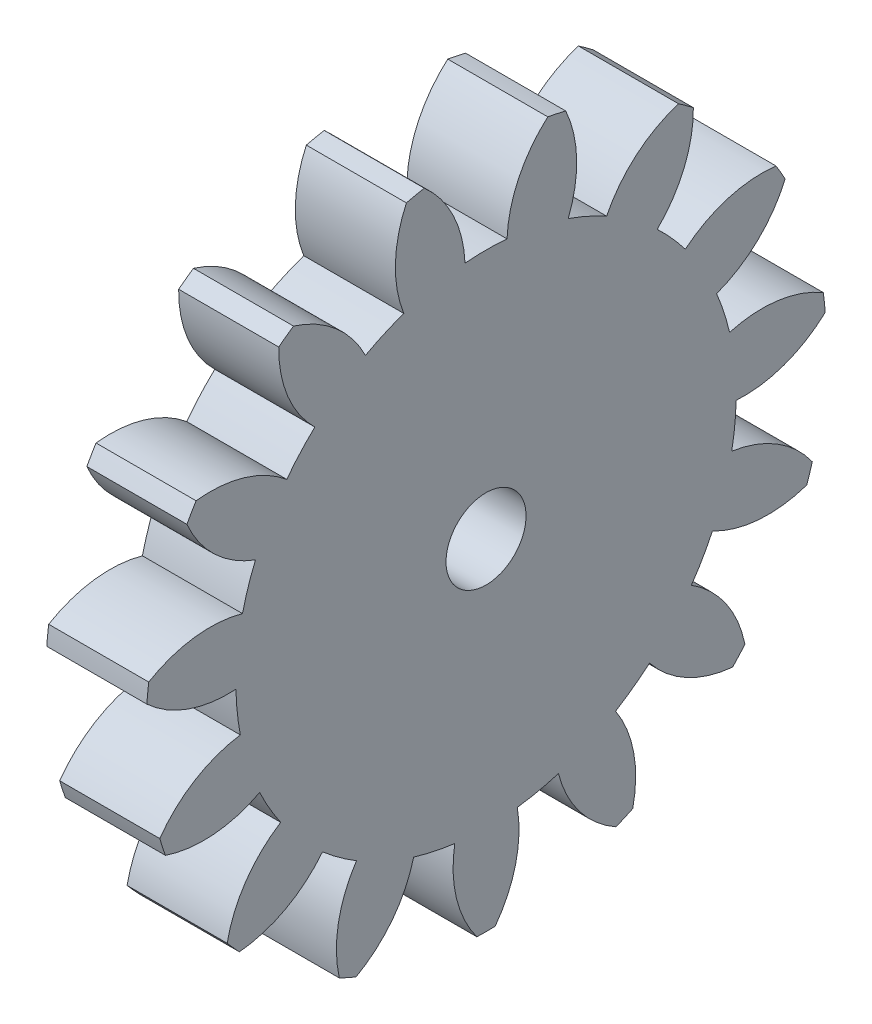
SolidWorks part; units mm, degrees
ref_plane "Plane1" through (0, 0, 0) normal (0, 0, 1) x (1, 0, 0)
ref_plane "Plane2" through (0, 0, 0) normal (0, 1, 0) x (1, 0, 0)
ref_plane "Plane3" through (0, 0, 0) normal (1, 0, 0) x (0, 0, -1)
sketch "HoldingSke" plane through (0, 0, 0) normal (0, 1, 0) x (1, 0, 0)
  line L0 (0, 0) -> (0.483, -0.1294)
  line L1 (-15, 0) -> (100, 0) construction
  line L2 (0, 0) -> (-2.1039, 2.3779)
  line L3 (0, 0) -> (-11.863, 4.5341)
  line L4 (0, 0) -> (8.3417, 2.2352)
  line L5 (0, 0) -> (-46.8476, -17.4728)
  line L6 (0, 0) -> (-4.1448, -2.7965)
  line L7 (-2.1039, 2.3779) -> (8.6586, 51.2059)
  line L8 (-76.2, 54.61) -> (-75.5, 54.61)
  line L9 (-71.009, 38.7566) -> (-53.1078, 45.2721)
  line L10 (-76.2, 71.12) -> (104.1128, 71.12)
  line L11 (0, 0) -> (-5, 0)
  line L12 (-76.2, 101.6) -> (-76.133, 101.6)
  line L13 (24.9733, 27.94) -> (52.9518, 28.4284)
  line L14 (24.9733, 27.94) -> (24.9743, 27.94)
  line L15 (24.9733, 27.94) -> (100.4006, 29.5858)
  line L16 (-63.627, -2) -> (-12.827, -2)
  circle A0 centre (0, 0) radius 2
  circle A1 centre (0, 0) radius 12.499
  circle A2 centre (0, 0) radius 37.5
  circle A3 centre (0, 0) radius 2
  dimension "MHD" = 24.998
  dimension "Hub_dia" = 75
  dimension "Bore" = 4
  dimension "MBD" = 4
  dimension "Num_teeth" = 15
  dimension "Pitch" = 0.5
  dimension "Overall_len" = 50
  dimension "Show_teeth" = 15
  dimension "Thickness" = 5
  dimension "OAL" = 50.0001
  dimension "T_dim" = 0.7
  dimension "Ap" = 20
  dimension "H" = 19.05
  dimension "Pitch_radius" = 180.3128
  dimension "Width" = 5
  dimension "Backlash" = 0.067
  dimension "Addendum_fac" = 1
  dimension "Dedendum_fac" = 1.25
  dimension "Clearance_fac" = 0.25
  dimension "Dedendum_add" = 0.001
  dimension "Module" = 2
sketch "BasProSke" plane through (0, 0, 0) normal (0, 1, 0) x (1, 0, 0)
  line L0 (-10, 0) -> (60, 0) construction
  line L1 (0, 0) -> (0, 17)
  line L2 (0, 0) -> (5, 0)
  line L3 (5, 0) -> (5, 17)
  line L4 (5, 17) -> (0, 17)
  dimension "Thickness" = 5
  dimension "Diameter" = 34
revolve "Base-Revolve" add sketch "BasProSke" angle 360 about L0
sketch "TooCutSke" plane through (0, 0, 0) normal (1, 0, 0) x (0, 0, -1)
  line L1 (0, 0) -> (0, 107) construction
  line L2 (0, 0) -> (-1.6851, 14.905) construction
  line L3 (0, 0) -> (-6.2081, 29.2069) construction
  line L4 (-1.6851, 14.905) -> (-3.1041, 14.6034) construction
  arc A0 (1.0501, 12.4548) -> (-1.0501, 12.4548) centre (0, 0) ccw
  arc A1 (3.1109, 16.7388) -> (-3.1109, 16.7388) centre (0, 0) ccw
  circle A2 centre (0, 0) radius 15 construction
  circle A3 centre (0, 0) radius 14.0954 construction
  arc A4 (-1.0501, 12.4548) -> (-3.1109, 16.7388) centre (-7.045, 12.2085) ccw
  arc A5 (3.1109, 16.7388) -> (1.0501, 12.4548) centre (7.045, 12.2085) ccw
  dimension "Root_dia" = 24.998
  dimension "Overcut_dia" = 34.0508
  dimension "Pitch_dia" = 30
  dimension "Base_dia" = 28.1908
  dimension "Flank_rad" = 6
  dimension "Half_ang" = 12
  dimension "Half_CT" = 1.4507
extrude "ToothCut" cut sketch "TooCutSke" along normal through all
fillet "Breaks" [suppressed] radius 0.04
fillet "RootFillets" [suppressed] radius 0.501
pattern_circular "TeethCuts" count 15 every 24 about axis through (-10, 0, 0) along (1, 0, 0) of "ToothCut", "RootFillets", "Breaks"
sketch "HubNeaOneSke" plane through (0, 0, 0) normal (-1, 0, 0) x (0, 0, 1)
  circle A0 centre (0, 0) radius 12.499
  dimension "Diameter" = 24.998
extrude "HubNearOne" [suppressed] add sketch "HubNeaOneSke" along normal blind 45.0001
sketch "HubNeaBotSke" plane through (0, 0, 0) normal (-1, 0, 0) x (0, 0, 1)
  circle A0 centre (0, 0) radius 12.499
  dimension "Diameter" = 24.998
extrude "HubNearBoth" [suppressed] add sketch "HubNeaBotSke" along normal blind 22.5
ref_plane "FarPln" through (5, 0, 0) normal (1, 0, 0) x (0, 0, -1)
sketch "HubFarSke" plane through (5, 0, 0) normal (1, 0, 0) x (0, 0, -1)
  circle A0 centre (0, 0) radius 12.499
  dimension "Diameter" = 24.998
extrude "HubFar" [suppressed] add sketch "HubFarSke" along normal blind 22.5
sketch "BorSke" plane through (0, 0, 0) normal (1, 0, 0) x (0, 0, -1)
  circle A0 centre (0, 0) radius 2
  dimension "Diameter" = 4
extrude "Bore" cut sketch "BorSke" along normal mid plane 100.0001
sketch "KeySke" plane through (0, 0, 0) normal (1, 0, 0) x (0, 0, -1)
  line L0 (-0.8, 0) -> (-0.8, 2.7)
  line L1 (-0.8, 2.7) -> (0.8, 2.7)
  line L2 (0.8, 2.7) -> (0.8, 0)
  line L3 (0, 0) -> (0, 34) construction
  line L4 (-0.8, 0) -> (0.8, 0)
  dimension "Offset" = 2.7
  dimension "Width" = 1.6
extrude "Keyway" [suppressed] cut sketch "KeySke" along normal mid plane 100.0001
pattern_circular "Keyway2" [suppressed] count 2 every 90 about axis through (-10, 0, 0) along (1, 0, 0)
equation "' \"Module@HoldingSke\" = 6.35"
equation "' \"Num_teeth@HoldingSke\" = 12"
equation "' \"Ap@HoldingSke\" =  20"
equation "' \"Ap@HoldingSke\" = 20"
equation "' \"Width@HoldingSke\" = 0.5 * 25.4"
equation "' \"Hub_dia@HoldingSke\"= 1 * 25.4"
equation "' \"Hub_dia@HoldingSke\" = 1 * 25.4"
equation "' \"Overall_len@HoldingSke\" = 1.0 * 25.4"
equation "' \"Bore@HoldingSke\" = 0.75 * 25.4"
equation "' \"T_dim@HoldingSke\" = 0.1 * 25.4"
equation "' \"Width@KeySke\" = 0.25 * 25.4"
equation "' \"Show_teeth@HoldingSke\" = 13"
equation "' \"Backlash@HoldingSke\" = 0.009 * 25.4"
equation "' \"Addendum_fac@HoldingSke\" = 1.0"
equation "' \"Dedendum_fac@HoldingSke\" = 1.25"
equation "' \"Dedendum_add@HoldingSke\" = 0.00005 * 25.4"
equation "' \"Clearance_fac@HoldingSke\" = 0.25"
equation "\"Pitch@HoldingSke\" = 1 / \"Module@HoldingSke\""
equation "\"Overcut_dia@TooCutSke\" = (\"Num_teeth@HoldingSke\" + 2 * \"Addendum_fac@HoldingSke\") / \"Pitch@HoldingSke\" + 0.002 * 25.4"
equation "\"Pitch_dia@TooCutSke\" = \"Num_teeth@HoldingSke\" / \"Pitch@HoldingSke\""
equation "\"Base_dia@TooCutSke\" = \"Num_teeth@HoldingSke\" / \"Pitch@HoldingSke\" * cos((\"Ap@HoldingSke\"  * 3.14159265 / 180))"
equation "\"Root_dia@TooCutSke\" = (\"Num_teeth@HoldingSke\" + 2) / \"Pitch@HoldingSke\" - 2 * (\"Addendum_fac@HoldingSke\" + \"Dedendum_fac@HoldingSke\") / \"Pitch@HoldingSke\" - \"Dedendum_add@HoldingSke\" * 2"
equation "\"Half_ang@TooCutSke\" = 180 / \"Num_teeth@HoldingSke\""
equation "\"Half_CT@TooCutSke\" = \"Num_teeth@HoldingSke\" / \"Pitch@HoldingSke\" * sin((3.14159265 / 2 / \"Num_teeth@HoldingSke\")) / 2 - 7 * \"Backlash@HoldingSke\" / 4"
equation "\"Flank_rad@TooCutSke\" = \"Num_teeth@HoldingSke\" / \"Pitch@HoldingSke\" / 5"
equation "\"Radius@RootFillets\" = \"Clearance_fac@HoldingSke\" / \"Pitch@HoldingSke\" + \"Dedendum_add@HoldingSke\""
equation "\"Break_rad@Breaks\" = 0.02 / \"Pitch@HoldingSke\""
equation "\"Thickness@HoldingSke\" = \"Width@HoldingSke\""
equation "\"OAL@HoldingSke\" = \"Thickness@HoldingSke\""
equation "\"MHD@HoldingSke\" = (\"Num_teeth@HoldingSke\" + 2) / \"Pitch@HoldingSke\" - 2 * (\"Addendum_fac@HoldingSke\" + \"Dedendum_fac@HoldingSke\")  / \"Pitch@HoldingSke\" - \"Dedendum_add@HoldingSke\" * 2"
equation "\"MBD@HoldingSke\" = (\"Num_teeth@HoldingSke\" + 2) / \"Pitch@HoldingSke\" - 2 * (\"Addendum_fac@HoldingSke\" + \"Dedendum_fac@HoldingSke\")  / \"Pitch@HoldingSke\" - \"Dedendum_add@HoldingSke\" * 2 - 0.002 * 25.4"
equation "\"MHD@HoldingSke\" = ((sgn( \"MHD@HoldingSke\" - \"Hub_dia@HoldingSke\" )-1)*( \"MHD@HoldingSke\" - \"Hub_dia@HoldingSke\" ))/-2+ \"Hub_dia@HoldingSke\""
equation "\"MBD@HoldingSke\" = ((sgn( \"MBD@HoldingSke\" - \"Bore@HoldingSke\" )-1)*( \"MBD@HoldingSke\" - \"Bore@HoldingSke\" ))/-2+ \"Bore@HoldingSke\""
equation "\"OAL@HoldingSke\" = ((sgn( \"OAL@HoldingSke\" - \"Overall_len@HoldingSke\" )+1)*( \"OAL@HoldingSke\" - \"Overall_len@HoldingSke\" ))/2 + \"Overall_len@HoldingSke\" + 0.000002 * 25.4"
equation "\"Num_teeth@TeethCuts\" = int( \"Show_teeth@HoldingSke\" ) + 1"
equation "\"Num_teeth@TeethCuts\" = ((sgn( \"Num_teeth@TeethCuts\" - \"Num_teeth@HoldingSke\" )-1)*( \"Num_teeth@TeethCuts\" - \"Num_teeth@HoldingSke\" ))/-2+ \"Num_teeth@HoldingSke\""
equation "\"Num_teeth@TeethCuts\" = ((sgn( \"Num_teeth@TeethCuts\" - 2.0)+1)*( \"Num_teeth@TeethCuts\" - 2.0))/2 +2.0"
equation "\"Angle@TeethCuts\" = 360.0 / \"Num_teeth@HoldingSke\""
equation "\"Diameter@BasProSke\" = (\"Num_teeth@HoldingSke\" + 2 * \"Addendum_fac@HoldingSke\") / \"Pitch@HoldingSke\""
equation "\"Thickness@BasProSke\"  = \"Thickness@HoldingSke\""
equation "' \"Fillet_rad@BasProSke\" =  \"Thickness@HoldingSke\" * 0.05"
equation "' \"Fillet_rad@BasProSke\" = \"Thickness@HoldingSke\" * 0.05"
equation "\"MHD@HoldingSke\" = ((sgn( \"MHD@HoldingSke\" - \"Root_dia@TooCutSke\" )-1)*( \"MHD@HoldingSke\" - \"Root_dia@TooCutSke\" ))/-2+ \"Root_dia@TooCutSke\""
equation "\"Diameter@HubNeaOneSke\" = \"MHD@HoldingSke\""
equation "\"Length@HubNearOne\" = \"OAL@HoldingSke\" - \"Thickness@BasProSke\""
equation "\"Diameter@HubNeaBotSke\" = \"MHD@HoldingSke\""
equation "\"Length@HubNearBoth\" = ( \"OAL@HoldingSke\" - \"Thickness@BasProSke\" ) / 2.0"
equation "\"Thickness@FarPln\" = \"Thickness@BasProSke\""
equation "\"Diameter@HubFarSke\" = \"MHD@HoldingSke\""
equation "\"Length@HubFar\" = ( \"OAL@HoldingSke\" - \"Thickness@BasProSke\" ) / 2.0"
equation "\"Diameter@BorSke\" = \"MBD@HoldingSke\""
equation "\"D1@Bore\" = \"OAL@HoldingSke\" * 2.0"
equation "\"D1@Keyway\" = \"OAL@HoldingSke\" * 2.0"
equation "\"Offset@KeySke\" = \"T_dim@HoldingSke\" + \"MBD@HoldingSke\" / 2.0"
